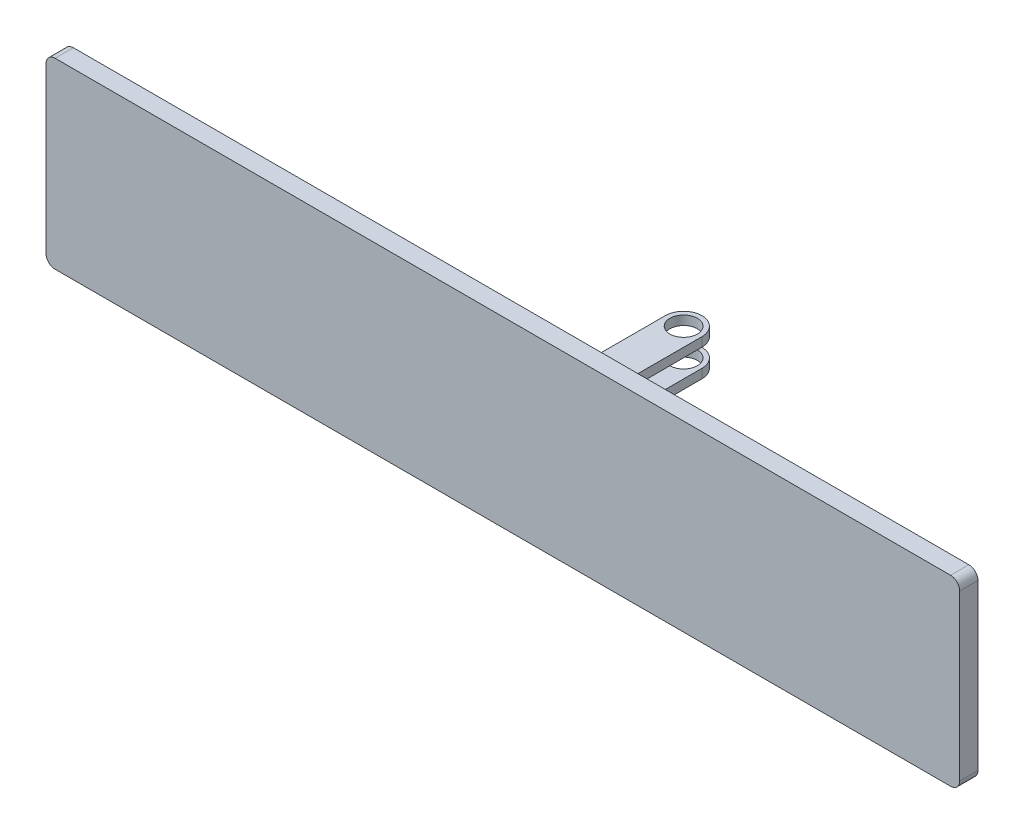
SolidWorks part; units mm, degrees
ref_plane "Front Plane" through (0, 0, 0) normal (0, 0, 1) x (1, 0, 0)
ref_plane "Top Plane" through (0, 0, 0) normal (0, 1, 0) x (1, 0, 0)
ref_plane "Right Plane" through (0, 0, 0) normal (1, 0, 0) x (0, 0, -1)
sketch "Sketch1" plane through (0, 0, 0) normal (0, 0, 1) x (1, 0, 0)
  line L1 (-45.049, 3.7512) -> (54.951, 3.7512)
  line L2 (-45.049, 3.7512) -> (-45.049, -16.2488)
  line L3 (-45.049, -16.2488) -> (54.951, -16.2488)
  line L4 (54.951, 3.7512) -> (54.951, -16.2488)
extrude "Boss-Extrude1" add sketch "Sketch1" along normal blind 2 contours L1 L4 L3 L2
ref_plane "Plane2" through (0, -7.2488, 0) normal (0, -1, 0) x (-1, 0, 0)
ref_plane "Plane3" through (0, -5.2488, 0) normal (0, 1, 0) x (1, 0, 0)
fillet "Fillet6" radius 1 1 edges at (54.951, -16.2488, 1)
fillet "Fillet7" radius 1 1 edges at (-45.049, -16.2488, 1)
fillet "Fillet8" radius 1 1 edges at (-45.049, 3.7512, 1)
fillet "Fillet9" radius 1 1 edges at (54.951, 3.7512, 1)
sketch "Sketch2" plane through (0, -7.2488, 0) normal (0, -1, 0) x (-1, 0, 0)
  line L0 (-9.731, 0) -> (-9.731, 15)
  line L1 (-9.731, 0) -> (-5.731, 0)
  line L2 (-5.731, 0) -> (-5.731, 15)
  arc A0 (-9.731, 15) -> (-5.731, 15) centre (-7.731, 15) cw
sketch "Sketch3" plane through (0, -5.2488, 0) normal (0, 1, 0) x (1, 0, 0)
  line L0 (5.731, 0) -> (5.731, 15)
  line L1 (5.731, 0) -> (9.731, 0)
  line L2 (9.731, 0) -> (9.731, 15)
  arc A0 (9.731, 15) -> (5.731, 15) centre (7.731, 15) ccw
extrude "Boss-Extrude2" add sketch "Sketch2" along normal blind 1 contours L0 A0 L2 L1
extrude "Boss-Extrude3" add sketch "Sketch3" along normal blind 1 contours L0 A0 L2 L1
sketch "Sketch4" plane through (0, -4.2488, 0) normal (0, 1, 0) x (1, 0, 0)
  circle A0 centre (7.731, 15) radius 1.5
  circle A1 centre (7.731, 5) radius 1.5
  dimension "D1" = 10
extrude "Cut-Extrude4" cut sketch "Sketch4" against normal blind 11
